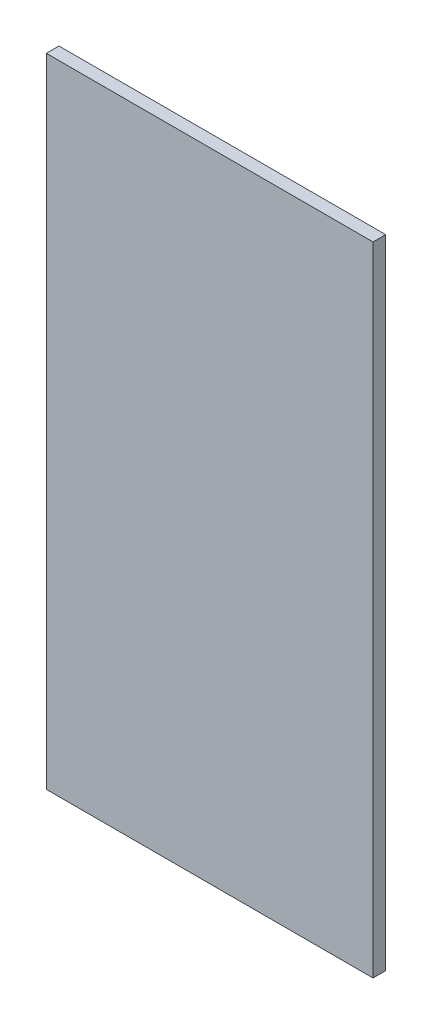
SolidWorks part; units mm, degrees
ref_plane "Front Plane" through (0, 0, 0) normal (0, 0, 1) x (1, 0, 0)
ref_plane "Top Plane" through (0, 0, 0) normal (0, 1, 0) x (1, 0, 0)
ref_plane "Right Plane" through (0, 0, 0) normal (1, 0, 0) x (0, 0, -1)
sketch "Sketch1" plane through (0, 0, 0) normal (0, 0, 1) x (1, 0, 0)
  line L1 (0, 0) -> (82, 0)
  line L2 (0, 0) -> (0, 160)
  line L3 (0, 160) -> (82, 160)
  line L4 (82, 0) -> (82, 160)
  dimension "D1" = 82
  dimension "D2" = 160
extrude "Boss-Extrude1" add sketch "Sketch1" along normal blind 3.175
